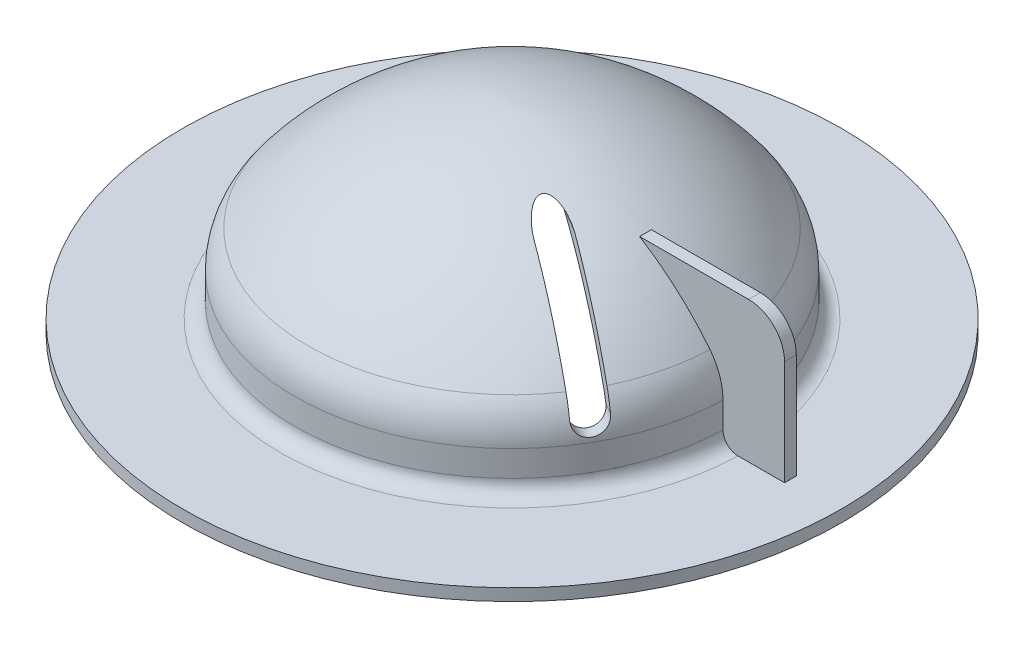
SolidWorks part; units mm, degrees
ref_plane "Front Plane" through (0, 0, 0) normal (0, 0, 1) x (1, 0, 0)
ref_plane "Top Plane" through (0, 0, 0) normal (0, 1, 0) x (1, 0, 0)
ref_plane "Right Plane" through (0, 0, 0) normal (1, 0, 0) x (0, 0, -1)
sketch "Sketch1" plane through (0, 0, 0) normal (0, 0, 1) x (1, 0, 0)
  line L0 (49.0977, -15.3268) -> (69.775, -15.3268)
  line L1 (0, 0) -> (0, 22.539) construction
  line L2 (43.3827, -4.1388) -> (43.3827, -9.6118)
  line L3 (0, 23.2766) -> (0, 25.8195)
  line L4 (45.9227, -4.1388) -> (45.9227, -9.6118)
  line L5 (49.0977, -12.7868) -> (69.775, -12.7868)
  line L6 (69.775, -12.7868) -> (69.775, -15.3268)
  line L7 (-1.1723, 17.4239) -> (59.6335, 17.4239) construction
  line L8 (59.6335, 17.4239) -> (59.6335, -2.4891) construction
  line L9 (59.6335, -2.4891) -> (-1.1723, -2.4891) construction
  arc A0 (43.1583, 3.7716) -> (0, 25.8195) centre (-2.7077, -32.7455) ccw
  arc A1 (43.1583, 3.7716) -> (45.9227, -4.1388) centre (33.2227, -4.1388) cw
  arc A2 (45.9227, -9.6118) -> (49.0977, -12.7868) centre (49.0977, -9.6118) ccw
  arc A3 (43.3827, -9.6118) -> (49.0977, -15.3268) centre (49.0977, -9.6118) ccw
  arc A4 (41.1712, 2.1895) -> (43.3827, -4.1388) centre (33.2227, -4.1388) cw
  arc A5 (41.1712, 2.1895) -> (0, 23.2766) centre (-2.7077, -32.7455) ccw
  arc A6 (41.1712, 2.1895) -> (-0.1173, 23.2822) centre (-2.7077, -32.7455) ccw construction
  dimension "D1" = 12.7
  dimension "D2" = 3.175
  dimension "D3" = 2.54
revolve "Revolve1" add sketch "Sketch1" angle 360 about L1
sketch "Sketch2" plane through (0, 0, 0) normal (0, 0, 1) x (1, 0, 0)
  line L0 (11.1233, 18.6468) -> (58.7758, 18.6468)
  line L1 (58.7758, 18.6468) -> (58.7758, -17.8219)
  line L2 (58.7758, -17.8219) -> (11.1233, -17.8219)
  line L3 (11.1233, -17.8219) -> (11.1233, 18.6468)
ref_plane "Plane1" through (58.928, 0, 0) normal (1, 0, 0) x (0, 0, -1)
sketch "Sketch4" plane through (58.928, 0, 0) normal (1, 0, 0) x (0, 0, -1)
  line L1 (0, -17.8219) -> (0, 18.6468) construction
  line L2 (-1.2438, 17.0355) -> (1.2438, 17.0355)
  line L3 (-1.2438, 17.0355) -> (-1.2438, -12.7868)
  line L4 (-1.2438, -12.7868) -> (1.2438, -12.7868)
  line L5 (1.2438, 17.0355) -> (1.2438, -12.7868)
  line L8 (69.775, -12.7868) -> (-69.775, -12.7868) construction
  point P2 (0, 2.1244)
extrude "Extrude4" add sketch "Sketch4" against normal up to body
fillet "Fillet1" radius 7.62 1 edges at (58.928, 17.0355, 0)
sketch "Sketch5" plane through (0, 0, 0) normal (0, 1, 0) x (1, 0, 0)
  line L0 (0, 0) -> (76.1436, -43.9615)
  line L1 (0, 0) -> (97.0733, 0)
  dimension "D1" = 30
ref_plane "Plane3" through (76.1436, 0, 43.9615) normal (0.866, 0, 0.5) x (0.5, 0, -0.866)
sketch "Sketch8" plane through (76.1436, 0, 43.9615) normal (0.866, 0, 0.5) x (0.5, 0, -0.866)
  line L1 (3.175, 0) -> (3.175, 19.05)
  line L2 (-3.175, 0) -> (-3.175, 19.05)
  line L3 (0, 0) -> (48.5367, 0) construction
  arc A0 (3.175, 19.05) -> (-3.175, 19.05) centre (0, 19.05) ccw
  arc A1 (-3.175, 0) -> (3.175, 0) centre (0, 0) ccw
  dimension "D1" = 19.05
extrude "Extrude5" cut sketch "Sketch8" against normal blind 74.422
